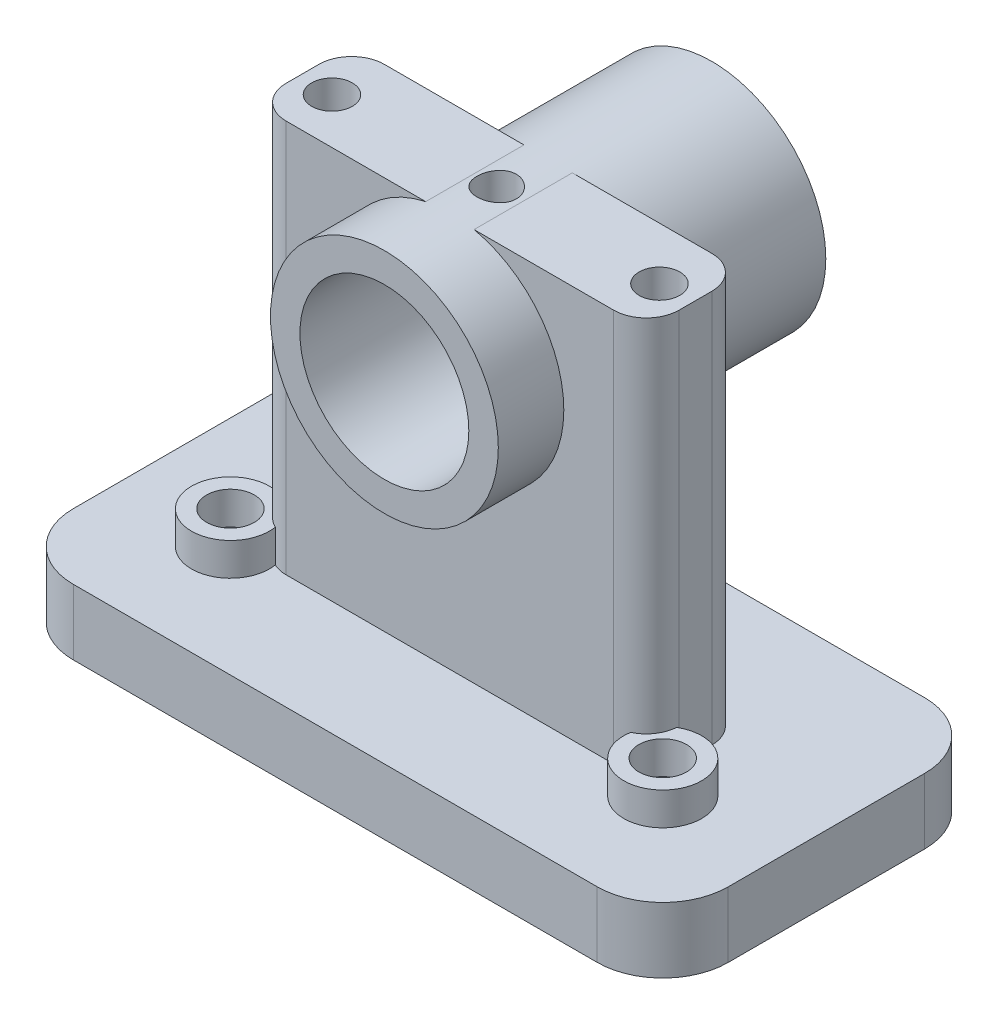
SolidWorks part; units mm, degrees
ref_plane "Front Plane" through (0, 0, 0) normal (0, 0, 1) x (1, 0, 0)
ref_plane "Top Plane" through (0, 0, 0) normal (0, 1, 0) x (1, 0, 0)
ref_plane "Right Plane" through (0, 0, 0) normal (1, 0, 0) x (0, 0, -1)
sketch "Sketch1" plane through (0, 0, 0) normal (0, 1, 0) x (1, 0, 0)
  line L1 (-38.6034, 28.352) -> (41.3966, 28.352)
  line L2 (-48.6034, 18.352) -> (-48.6034, -11.648)
  line L3 (-38.6034, -21.648) -> (41.3966, -21.648)
  line L4 (51.3966, 18.352) -> (51.3966, -11.648)
  arc A0 (41.3966, 28.352) -> (51.3966, 18.352) centre (41.3966, 18.352) cw
  arc A1 (41.3966, -21.648) -> (51.3966, -11.648) centre (41.3966, -11.648) ccw
  arc A2 (-48.6034, -11.648) -> (-38.6034, -21.648) centre (-38.6034, -11.648) ccw
  arc A3 (-38.6034, 28.352) -> (-48.6034, 18.352) centre (-38.6034, 18.352) ccw
  point P6 (51.3966, 28.352)
  point P11 (-48.6034, -21.648)
  point P14 (-48.6034, 28.352)
  dimension "D3" = 10
  dimension "D1" = 100
  dimension "D2" = 50
extrude "Boss-Extrude2" add sketch "Sketch1" along normal blind 10
sketch "Sketch3" plane through (0, 10, 0) normal (0, 1, 0) x (1, 0, 0)
  line L0 (-38.6034, -21.648) -> (41.3966, -21.648) construction
  line L1 (-23.6034, 10.852) -> (26.3966, 10.852)
  line L2 (-28.6034, 5.852) -> (-28.6034, 0.852)
  line L3 (-23.6034, -4.148) -> (26.3966, -4.148)
  line L4 (31.3966, 5.852) -> (31.3966, 0.852)
  line L5 (-48.6034, 18.352) -> (-48.6034, -11.648) construction
  line L6 (51.3966, -11.648) -> (51.3966, 18.352) construction
  line L7 (41.3966, 28.352) -> (-38.6034, 28.352) construction
  arc A0 (26.3966, 10.852) -> (31.3966, 5.852) centre (26.3966, 5.852) cw
  arc A1 (26.3966, -4.148) -> (31.3966, 0.852) centre (26.3966, 0.852) ccw
  arc A2 (-28.6034, 0.852) -> (-23.6034, -4.148) centre (-23.6034, 0.852) ccw
  arc A3 (-23.6034, 10.852) -> (-28.6034, 5.852) centre (-23.6034, 5.852) ccw
  dimension "D5" = 5
  dimension "D1" = 17.5
  dimension "D2" = 20
  dimension "D3" = 20
  dimension "D4" = 17.5
extrude "Boss-Extrude4" add sketch "Sketch3" along normal blind 60
sketch "Sketch4" plane through (0, 10, 0) normal (0, 1, 0) x (1, 0, 0)
  line L0 (51.3966, -11.648) -> (51.3966, 18.352) construction
  line L1 (-38.6034, -21.648) -> (41.3966, -21.648) construction
  line L2 (1.3966, 28.352) -> (1.3966, -21.648) construction
  line L3 (41.3966, 28.352) -> (-38.6034, 28.352) construction
  circle A0 centre (34.3966, -4.648) radius 3.6402
  circle A1 centre (34.3966, -4.648) radius 5.9504
  circle A3 centre (-31.6034, -4.648) radius 5.9504
  circle A4 centre (-31.6034, -4.648) radius 3.6402
  dimension "D1" = 17
  dimension "D2" = 17
extrude "Boss-Extrude5" add sketch "Sketch4" along normal blind 5
ref_plane "Plane3" through (0, 0, 14.148) normal (0, 0, 1) x (1, 0, 0)
sketch "Sketch9" plane through (0, 0, 14.148) normal (0, 0, 1) x (1, 0, 0)
  line L0 (31.3966, 70) -> (31.3966, 10) construction
  line L1 (-23.6034, 10) -> (26.3966, 10) construction
  circle A0 centre (1.3966, 53) radius 17.3964
  circle A1 centre (1.3966, 53) radius 12.893
  point P5 (31.3966, 40)
  dimension "D1" = 30
  dimension "D2" = 43
extrude "Boss-Extrude7" add sketch "Sketch9" against normal blind 50
sketch "Sketch11" plane through (0, 0, 4.148) normal (0, 0, 1) x (1, 0, 0)
  circle A1 centre (1.3966, 53) radius 12.893
  circle A2 centre (1.3966, 53) radius 12.893
  dimension "D1" = 0
extrude "Cut-Extrude2" cut sketch "Sketch11" against normal through all
sketch "Sketch12" plane through (0, 70, 0) normal (0, 1, 0) x (1, 0, 0)
  line L0 (5.089, -4.148) -> (26.3966, -4.148) construction
  line L1 (31.3966, 0.852) -> (31.3966, 5.852) construction
  line L2 (1.3966, 35.852) -> (1.3966, -21.648) construction
  line L3 (14.2897, 35.852) -> (-11.4964, 35.852) construction
  line L4 (-38.6034, -21.648) -> (41.3966, -21.648) construction
  circle A0 centre (26.3966, 2.852) radius 3.1088
  circle A1 centre (-23.6034, 2.852) radius 3.1088
  dimension "D1" = 7
  dimension "D2" = 5
extrude "Cut-Extrude5" cut sketch "Sketch12" against normal blind 63
ref_plane "Plane4" through (0, 75, 0) normal (0, 1, 0) x (1, 0, 0)
ref_plane "Plane5" through (0, 75, 0) normal (0, 1, 0) x (1, 0, 0)
sketch "Sketch16" plane through (0, 75, 0) normal (0, 1, 0) x (1, 0, 0)
  circle A0 centre (1.3966, 2.9966) radius 3.0047
extrude "Cut-Extrude6" cut sketch "Sketch16" against normal blind 66
